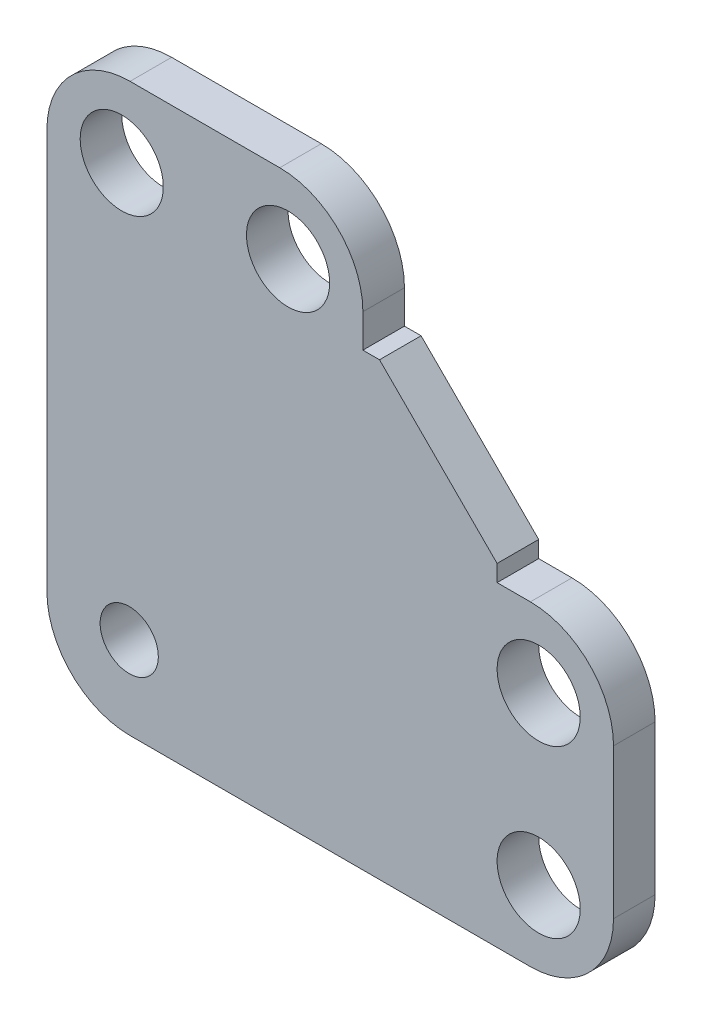
SolidWorks part; units mm, degrees
ref_plane "Plan de face" through (0, 0, 0) normal (0, 0, 1) x (1, 0, 0)
ref_plane "Plan de dessus" through (0, 0, 0) normal (0, 1, 0) x (1, 0, 0)
ref_plane "Plan de droite" through (0, 0, 0) normal (1, 0, 0) x (0, 0, -1)
sketch "Esquisse1" plane through (0, 0, 0) normal (0, 0, 1) x (1, 0, 0)
  line L0 (0, 0) -> (54.1421, 0)
  line L1 (54.1421, 0) -> (54.1421, 40)
  line L2 (54.1421, 40) -> (40, 54.1421)
  line L3 (40, 54.1421) -> (0, 54.1421)
  line L4 (0, 54.1421) -> (0, 0)
  dimension "D1" = 135
  dimension "D2" = 20
  dimension "D3" = 40
extrude "Boss.-Extru.1" add sketch "Esquisse1" along normal blind 5
sketch "Esquisse3" plane through (0, 0, 5) normal (0, 0, 1) x (1, 0, 0)
  line L0 (47.0711, 47.0711) -> (0, 0) construction
  line L1 (0, 54.1421) -> (38, 54.1421)
  line L2 (0, 54.1421) -> (0, 68.1421)
  line L3 (0, 68.1421) -> (38, 68.1421)
  line L4 (38, 54.1421) -> (38, 68.1421)
  line L5 (54.1421, 40) -> (40, 54.1421) construction
  line L6 (54.1421, 38) -> (68.1421, 38)
  line L7 (68.1421, 0) -> (68.1421, 38)
  line L8 (54.1421, 0) -> (68.1421, 0)
  line L9 (54.1421, 0) -> (54.1421, 38)
  dimension "D1" = 2
  dimension "D2" = 14
extrude "Boss.-Extru.2" add sketch "Esquisse3" against normal up to vertex (5 mm away)
sketch "Esquisse4" plane through (0, 0, 5) normal (0, 0, 1) x (1, 0, 0)
  line L0 (38, 54.1421) -> (0, 54.1421) construction
  line L1 (0, 68.1421) -> (0, 0) construction
  line L2 (19, 54.1421) -> (19, 38.3704) construction
  line L3 (47.0711, 47.0711) -> (0, 0) construction
  line L4 (54.1421, 40) -> (40, 54.1421) construction
  line L5 (54.1421, 38) -> (54.1421, 0) construction
  circle A0 centre (29, 59.1421) radius 5
  circle A1 centre (9, 59.1421) radius 5
  circle A2 centre (59.1421, 9) radius 5
  circle A3 centre (59.1421, 29) radius 5
  circle A4 centre (9.8995, 9.8995) radius 3.5
  dimension "D1" = 20
  dimension "D2" = 10
  dimension "D3" = 14
  dimension "D4" = 7
extrude "Enlèv. mat.-Extru.2" cut sketch "Esquisse4" against normal through all
fillet "Congé1" radius 10 5 edges at (0, 0, 2.5) (68.1421, 0, 2.5) (68.1421, 38, 2.5) (0, 68.1421, 2.5) (38, 68.1421, 2.5)
